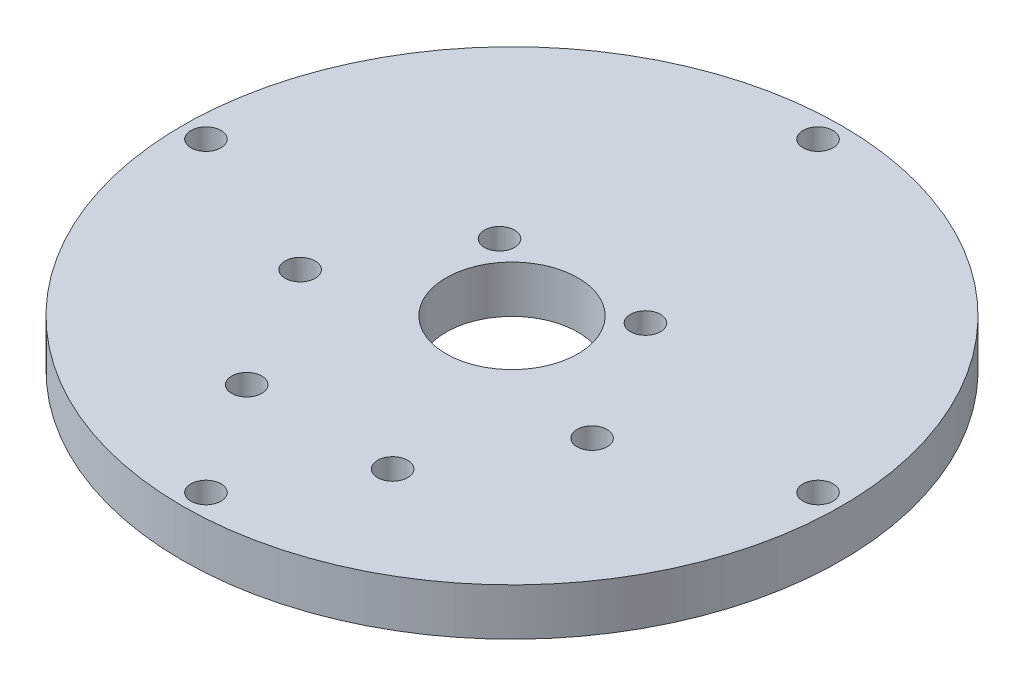
SolidWorks part; units mm, degrees
ref_plane "正面" through (0, 0, 0) normal (0, 0, 1) x (1, 0, 0)
ref_plane "平面" through (0, 0, 0) normal (0, 1, 0) x (1, 0, 0)
ref_plane "右側面" through (0, 0, 0) normal (1, 0, 0) x (0, 0, -1)
sketch "ｽｹｯﾁ1" plane through (0, 0, 0) normal (0, 1, 0) x (1, 0, 0)
  circle A0 centre (0, 0) radius 35
  dimension "D1" = 70
extrude "ﾎﾞｽ - 押し出し1" add sketch "ｽｹｯﾁ1" along normal blind 5 contours A0
sketch "ｽｹｯﾁ3" plane through (0, 5, 0) normal (0, 1, 0) x (1, 0, 0)
  circle A0 centre (-32.5, 0) radius 1.6
  circle A1 centre (0, 32.5) radius 1.6
  circle A2 centre (32.5, 0) radius 1.6
  circle A3 centre (0, -32.5) radius 1.6
  circle A4 centre (0, 0) radius 32.5 construction
  point P11 (0, 0)
  point P12 (0, 0)
  point P13 (0, 0)
  point P14 (0, 0)
  point P15 (0, 0)
  point P16 (0, 0)
  dimension "D1" = 65
  dimension "D2" = 3.2
extrude "ｶｯﾄ - 押し出し1" cut sketch "ｽｹｯﾁ3" against normal through all
sketch "ｽｹｯﾁ4" plane through (0, 5, 0) normal (0, 1, 0) x (1, 0, 0)
  circle A0 centre (0, 0) radius 7
  circle A1 centre (0, -7) radius 15.5 construction
  circle A2 centre (-15.5, -7) radius 1.6
  circle A3 centre (-7.75, 6.4234) radius 1.6
  circle A4 centre (7.75, 6.4234) radius 1.6
  circle A5 centre (15.5, -7) radius 1.6
  circle A6 centre (7.75, -20.4234) radius 1.6
  circle A7 centre (-7.75, -20.4234) radius 1.6
  circle A8 centre (0, -7) radius 18.5 construction
  point P19 (0, -7)
  dimension "D1" = 31
  dimension "D3" = 14
  dimension "D4" = 3.2
  dimension "D6" = 37
  dimension "D2" = 7
  dimension "D5" = 6
extrude "ｶｯﾄ - 押し出し2" cut sketch "ｽｹｯﾁ4" against normal through all
